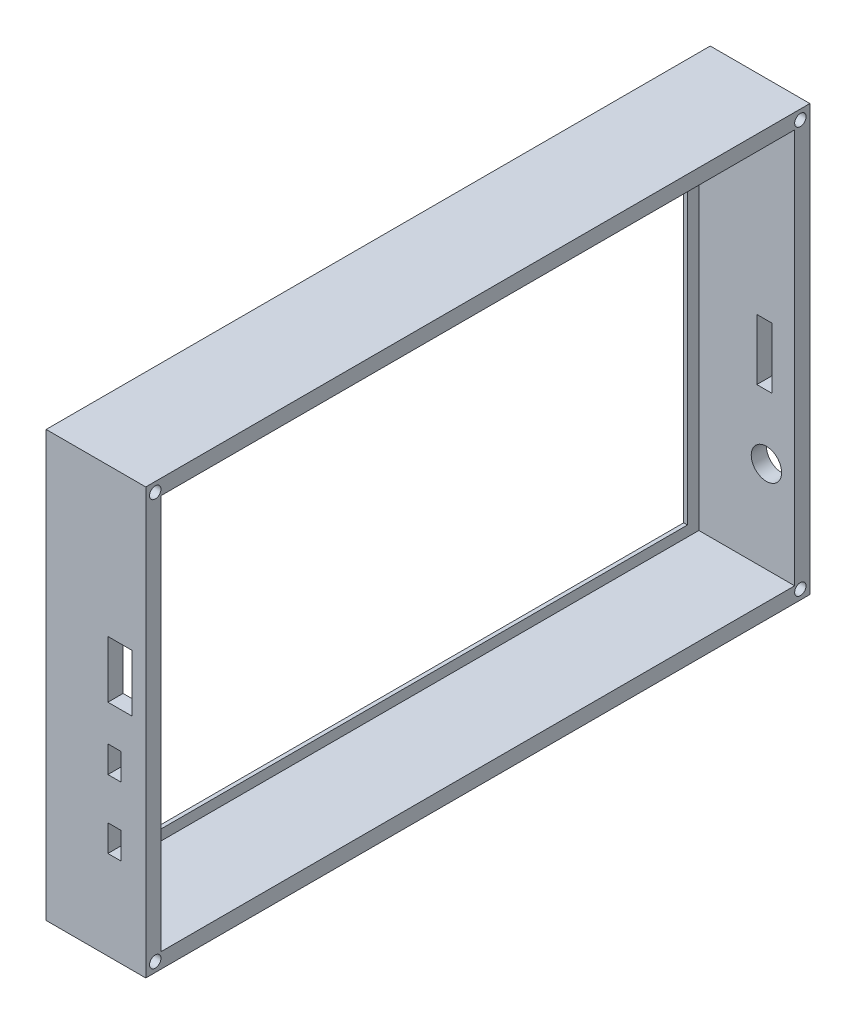
SolidWorks part; units mm, degrees
ref_plane "Alzado" through (0, 0, 0) normal (0, 0, 1) x (1, 0, 0)
ref_plane "Planta" through (0, 0, 0) normal (0, 1, 0) x (1, 0, 0)
ref_plane "Vista lateral" through (0, 0, 0) normal (1, 0, 0) x (0, 0, -1)
sketch "Croquis1" plane through (0, 0, 0) normal (1, 0, 0) x (0, 0, -1)
  line L1 (82.45, -51) -> (-82.45, -51)
  line L2 (82.45, -51) -> (82.45, 51)
  line L3 (82.45, 51) -> (-82.45, 51)
  line L4 (-82.45, -51) -> (-82.45, 51)
  point P0 (0, 0)
  point P5 (0, 0)
  dimension "D1" = 102
  dimension "D2" = 164.9
extrude "Saliente-Extruir2" add sketch "Croquis1" along normal blind 14.27
sketch "Croquis2" plane through (0, 0, 0) normal (1, 0, 0) x (0, 0, -1)
  line L0 (82.45, -51) -> (82.45, 51) construction
  line L5 (87.45, 56) -> (-87.45, 56)
  line L6 (87.45, 56) -> (87.45, -56)
  line L7 (87.45, -56) -> (-87.45, -56)
  line L8 (-87.45, 56) -> (-87.45, -56)
  line L9 (-82.45, 51) -> (-82.45, -51) construction
  line L10 (82.45, 51) -> (-82.45, 51) construction
  line L11 (-82.45, -51) -> (82.45, -51) construction
  line L13 (83.45, 52) -> (-83.45, 52)
  line L14 (83.45, 52) -> (83.45, -52)
  line L15 (83.45, -52) -> (-83.45, -52)
  line L16 (-83.45, 52) -> (-83.45, -52)
  dimension "D1" = 5
  dimension "D2" = 5
  dimension "D3" = 5
  dimension "D4" = 5
  dimension "D5" = 1
  dimension "D6" = 1
  dimension "D7" = 1
  dimension "D8" = 1
extrude "Saliente-Extruir3" add sketch "Croquis2" along normal blind 14.27 separate body
sketch "Croquis3" plane through (0, 0, 0) normal (-1, 0, 0) x (0, 0, 1)
  line L0 (83.45, 52) -> (83.45, -52) construction
  line L1 (-87.45, 56) -> (87.45, 56)
  line L2 (-87.45, 56) -> (-87.45, -56)
  line L3 (-87.45, -56) -> (87.45, -56)
  line L4 (87.45, 56) -> (87.45, -56)
  line L5 (-80.45, 49.125) -> (80.45, 49.125)
  line L6 (-80.45, 49.125) -> (-80.45, -49.2494)
  line L7 (-80.45, -49.2494) -> (80.45, -49.2494)
  line L8 (80.45, 49.125) -> (80.45, -49.2494)
  line L9 (-83.45, -52) -> (-83.45, 52) construction
  line L10 (-83.45, 52) -> (83.45, 52) construction
  line L11 (83.45, -52) -> (-83.45, -52) construction
  dimension "D1" = 160.9
  dimension "D2" = 3
  dimension "D3" = 3
  dimension "D4" = 2.875
  dimension "D5" = 2.7506
extrude "Saliente-Extruir5" add sketch "Croquis3" along normal blind 1
sketch "Croquis4" plane through (14.27, 0, 0) normal (1, 0, 0) x (0, 0, -1)
  line L1 (-82.45, 51) -> (82.45, 51)
  line L2 (-82.45, 51) -> (-82.45, -51)
  line L3 (-82.45, -51) -> (82.45, -51)
  line L4 (82.45, 51) -> (82.45, -51)
extrude "Cortar-Extruir2" cut sketch "Croquis4" against normal blind 14.27
sketch "Croquis6" plane through (14.27, 0, 0) normal (1, 0, 0) x (0, 0, -1)
  line L1 (-87.45, 56) -> (87.45, 56)
  line L2 (-87.45, 56) -> (-87.45, -56)
  line L3 (-87.45, -56) -> (87.45, -56)
  line L4 (87.45, 56) -> (87.45, -56)
  circle A0 centre (-77.445, 46) radius 1.5
  circle A1 centre (-77.445, -46) radius 1.5
  circle A2 centre (-22.1, 15.81) radius 1.5
  circle A3 centre (35.9, 15.81) radius 1.5
  circle A4 centre (-22.1, -33.19) radius 1.5
  circle A5 centre (35.9, -33.19) radius 1.5
  circle A6 centre (77.445, 46) radius 1.5
  circle A7 centre (77.445, -46) radius 1.5
  dimension "D1" = 3
  dimension "D2" = 3
extrude "Saliente-Extruir6" add sketch "Croquis6" along normal blind 15
sketch "Croquis8" plane through (14.27, 0, 0) normal (-1, 0, 0) x (0, 0, 1)
  line L1 (-80.45, 49.125) -> (80.45, 49.125)
  line L2 (-80.45, 49.125) -> (-80.45, -49.2494)
  line L3 (-80.45, -49.2494) -> (80.45, -49.2494)
  line L4 (80.45, 49.125) -> (80.45, -49.2494)
extrude "Cortar-Extruir3" cut sketch "Croquis8" against normal blind 9
sketch "Croquis9" plane through (14.27, 0, 0) normal (-1, 0, 0) x (0, 0, 1)
  line L1 (-83.45, 52) -> (83.45, 52)
  line L2 (-83.45, 52) -> (-83.45, -52)
  line L3 (-83.45, -52) -> (83.45, -52)
  line L4 (83.45, 52) -> (83.45, -52)
extrude "Cortar-Extruir5" cut sketch "Croquis9" against normal blind 11
sketch "Croquis15" plane through (0, 0, 87.45) normal (0, 0, 1) x (1, 0, 0)
  line L0 (21.57, 16.9173) -> (15.27, 16.9173)
  line L1 (15.27, 16.9173) -> (15.27, 1.9173)
  line L2 (15.27, 1.9173) -> (21.57, 1.9173)
  line L3 (21.57, 1.9173) -> (21.57, 16.9173)
  line L4 (15.27, -7.5827) -> (18.77, -7.5827)
  line L5 (18.77, -7.5827) -> (18.77, -14.5827)
  line L6 (18.77, -14.5827) -> (15.27, -14.5827)
  line L7 (15.27, -14.5827) -> (15.27, -7.5827)
  line L8 (18.77, -25.5827) -> (18.77, -32.5827)
  line L9 (18.77, -32.5827) -> (15.27, -32.5827)
  line L10 (15.27, -32.5827) -> (15.27, -25.5827)
  line L11 (15.27, -25.5827) -> (18.77, -25.5827)
  dimension "D1" = 6.3
  dimension "D2" = 3.5
  dimension "D3" = 3.5
extrude "Cortar-Extruir6" cut sketch "Croquis15" against normal blind 7
sketch "Croquis16" plane through (29.27, 0, 0) normal (1, 0, 0) x (0, 0, -1)
  line L1 (-70.6759, 19.4509) -> (-40.1252, 19.4509)
  line L2 (-35.1252, 24.4509) -> (-35.1252, 43.3705)
  line L3 (-40.1252, 48.3705) -> (-70.6759, 48.3705)
  line L5 (-75.6759, 43.3705) -> (-75.6759, 24.4509)
  line L6 (40.2695, 19.4658) -> (70.8201, 19.4658)
  line L7 (75.8201, 24.4658) -> (75.8201, 43.3853)
  line L8 (70.8201, 48.3853) -> (40.2695, 48.3853)
  line L9 (35.2695, 43.3853) -> (35.2695, 24.4658)
  arc A0 (-40.1252, 48.3705) -> (-35.1252, 43.3705) centre (-40.1252, 43.3705) cw
  arc A1 (-35.1252, 24.4509) -> (-40.1252, 19.4509) centre (-40.1252, 24.4509) cw
  arc A2 (-75.6759, 24.4509) -> (-70.6759, 19.4509) centre (-70.6759, 24.4509) ccw
  arc A3 (-75.6759, 43.3705) -> (-70.6759, 48.3705) centre (-70.6759, 43.3705) cw
  arc A4 (70.8201, 48.3853) -> (75.8201, 43.3853) centre (70.8201, 43.3853) cw
  arc A5 (75.8201, 24.4658) -> (70.8201, 19.4658) centre (70.8201, 24.4658) cw
  arc A6 (35.2695, 24.4658) -> (40.2695, 19.4658) centre (40.2695, 24.4658) ccw
  arc A7 (35.2695, 43.3853) -> (40.2695, 48.3853) centre (40.2695, 43.3853) cw
  dimension "D1" = 5
  dimension "D2" = 5
extrude "Cortar-Extruir7" cut sketch "Croquis16" against normal blind 7
sketch "Croquis17" plane through (0, 0, -87.45) normal (0, 0, -1) x (-1, 0, 0)
  circle A0 centre (-17.7917, -27.9017) radius 4
  dimension "D1" = 8
extrude "Cortar-Extruir8" cut sketch "Croquis17" against normal blind 7
sketch "Croquis18" plane through (0, 0, -87.45) normal (0, 0, -1) x (-1, 0, 0)
  line L1 (-19.27, 4.9173) -> (-15.27, 4.9173)
  line L2 (-19.27, 4.9173) -> (-19.27, -11.0827)
  line L3 (-19.27, -11.0827) -> (-15.27, -11.0827)
  line L4 (-15.27, 4.9173) -> (-15.27, -11.0827)
extrude "Cortar-Extruir9" cut sketch "Croquis18" against normal blind 7
sketch "Croquis21" plane through (29.27, 0, 0) normal (1, 0, 0) x (0, 0, -1)
  line L0 (-87.45, 56) -> (-87.45, -56) construction
  line L1 (87.45, 56) -> (-87.45, 56) construction
  line L2 (87.45, -56) -> (87.45, 56) construction
  line L3 (-87.45, -56) -> (87.45, -56) construction
  circle A0 centre (-84.95, 53.5) radius 1.5
  circle A1 centre (84.95, 53.5) radius 1.5
  circle A2 centre (84.95, -53.5) radius 1.5
  circle A3 centre (-84.95, -53.5) radius 1.5
  dimension "D1" = 3
  dimension "D4" = 3
  dimension "D7" = 3
  dimension "D10" = 3
  dimension "D2" = 2.5
  dimension "D3" = 2.5
  dimension "D5" = 2.5
  dimension "D6" = 2.5
  dimension "D8" = 2.5
  dimension "D9" = 2.5
  dimension "D11" = 2.5
  dimension "D12" = 2.5
extrude "Cortar-Extruir12" cut sketch "Croquis21" against normal blind 25.4
sketch "Croquis22" plane through (0, 0, -87.45) normal (0, 0, -1) x (-1, 0, 0)
  line L0 (-29.27, -56) -> (1, -56) construction
  line L1 (-29.27, 56) -> (-25.2359, 56)
  line L2 (-29.27, 56) -> (-29.27, -56)
  line L3 (-29.27, -56) -> (-25.2359, -56)
  line L4 (-25.2359, 56) -> (-25.2359, -56)
  dimension "D1" = 4.0341
extrude "Cortar-Extruir13" cut sketch "Croquis22" against normal blind 179.4
